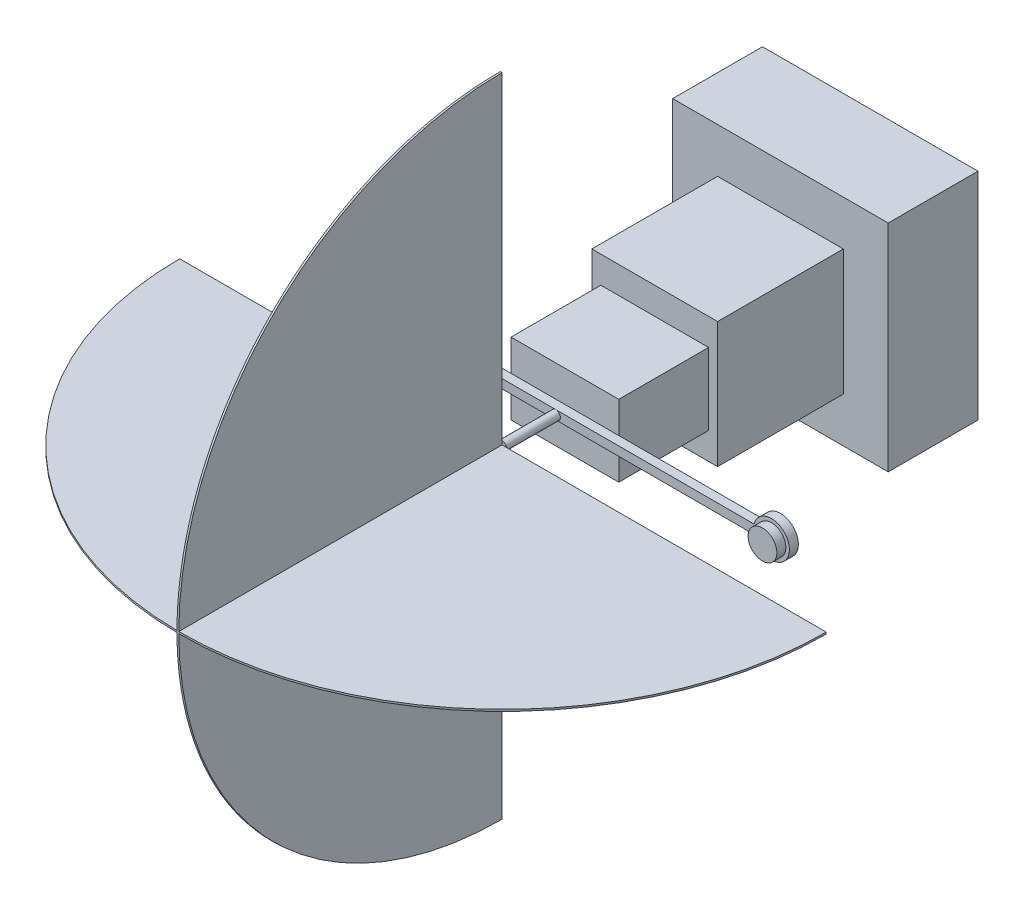
SolidWorks part; units mm, degrees
ref_plane "前视" through (0, 0, 0) normal (0, 0, 1) x (1, 0, 0)
ref_plane "上视" through (0, 0, 0) normal (0, 1, 0) x (1, 0, 0)
ref_plane "右视" through (0, 0, 0) normal (1, 0, 0) x (0, 0, -1)
sketch "草图1" plane through (0, 0, 0) normal (0, 0, 1) x (1, 0, 0)
  line L1 (-120, -2.5) -> (120, -2.5)
  line L2 (-120, -2.5) -> (-120, 2.5)
  line L3 (-120, 2.5) -> (120, 2.5)
  line L4 (120, -2.5) -> (120, 2.5)
  line L5 (-120, -2.5) -> (120, 2.5) construction
  line L6 (-120, 2.5) -> (120, -2.5) construction
  line L7 (-30, 20) -> (30, 20)
  line L8 (-30, 20) -> (-30, -20)
  line L9 (-30, -20) -> (30, -20)
  line L10 (30, 20) -> (30, -20)
  line L11 (-30, 20) -> (30, -20) construction
  line L12 (-30, -20) -> (30, 20) construction
  circle A0 centre (-120, 0) radius 10
  circle A1 centre (120, 0) radius 10
  point P0 (0, 0)
  point P10 (0, 0)
extrude "凸台-拉伸2" add sketch "草图1" along normal blind 5 contours L3 A0 L1 L2 | L1 A0 L3 L2 | A0 L1 L8 L3 | L1 A1 L3 L4
sketch "草图3" plane through (0, 0, 5) normal (0, 0, 1) x (1, 0, 0)
  circle A0 centre (-120, 0) radius 8
  circle A1 centre (120, 0) radius 8
extrude "凸台-拉伸3" add sketch "草图3" along normal blind 5
sketch "草图4" plane through (0, 0, 0) normal (0, 0, -1) x (-1, 0, 0)
  line L1 (-30, -20) -> (30, -20)
  line L2 (-30, -20) -> (-30, 20)
  line L3 (-30, 20) -> (30, 20)
  line L4 (30, -20) -> (30, 20)
  line L5 (-30, -20) -> (30, 20) construction
  line L6 (-30, 20) -> (30, -20) construction
  point P0 (0, 0)
extrude "凸台-拉伸4" add sketch "草图4" along normal blind 50
sketch3d "URDF Reference"
  line L0 (0, 0, 0) -> (10, 0, 0) construction
  line L1 (0, 0, 0) -> (0, 10, 0) construction
  point P0 (0, 0, 0)
  point P1 (0, 0, 0)
sketch "草图5" plane through (0, 0, -50) normal (0, 0, -1) x (-1, 0, 0)
  line L1 (-35, 35) -> (35, 35)
  line L2 (-35, 35) -> (-35, -35)
  line L3 (-35, -35) -> (35, -35)
  line L4 (35, 35) -> (35, -35)
  line L5 (-35, 35) -> (35, -35) construction
  line L6 (-35, -35) -> (35, 35) construction
  point P0 (0, 0)
extrude "凸台-拉伸5" add sketch "草图5" along normal blind 30
sketch "草图6" plane through (0, 0, 5) normal (0, 0, 1) x (1, 0, 0)
  circle A0 centre (0, 0) radius 2.5
extrude "凸台-拉伸6" add sketch "草图6" along normal blind 30
sketch3d "3D草图2" plane through (0, 0, 0) normal (0, 0, 1) x (1, 0, 0)
sketch "草图10" plane through (0, 0, 0) normal (0, -1, 0) x (-1, 0, 0)
  line L0 (179.5, -35) -> (-180.5, -35)
  arc A0 (179.5, -35) -> (-180.5, -35) centre (-0.5, -35) cw
extrude "凸台-拉伸11" add sketch "草图10" along normal blind 0.5 and the other way blind 0.5
sketch "草图11" plane through (-0.5, 0, 0) normal (-1, 0, 0) x (0, 0, 1)
  line L0 (35, 180) -> (35, -180)
  line L1 (35, 0.5) -> (35, -0.5) construction
  arc A0 (35, -180) -> (35, 180) centre (35, 0) ccw
extrude "凸台-拉伸12" add sketch "草图11" along normal blind 0.5 and the other way blind 0.5
sketch "草图12" plane through (0, 0, -80) normal (0, 0, -1) x (-1, 0, 0)
  line L0 (-35, -35) -> (35, -35) construction
  line L1 (-35, 35) -> (35, 35)
  line L2 (-35, 35) -> (-35, -35)
  line L3 (-35, -35) -> (35, -35)
  line L4 (35, 35) -> (35, -35)
  line L5 (-35, 35) -> (35, -35) construction
  line L6 (-35, -35) -> (35, 35) construction
  line L7 (35, -35) -> (35, 35) construction
  point P0 (0, 0)
extrude "凸台-拉伸13" add sketch "草图12" along normal blind 40
sketch "草图13" plane through (0, 0, -120) normal (0, 0, -1) x (-1, 0, 0)
  line L1 (-60, -60) -> (60, -60)
  line L2 (-60, -60) -> (-60, 60)
  line L3 (-60, 60) -> (60, 60)
  line L4 (60, -60) -> (60, 60)
  line L5 (-60, -60) -> (60, 60) construction
  line L6 (-60, 60) -> (60, -60) construction
  point P0 (0, 0)
extrude "凸台-拉伸14" add sketch "草图13" along normal blind 50
